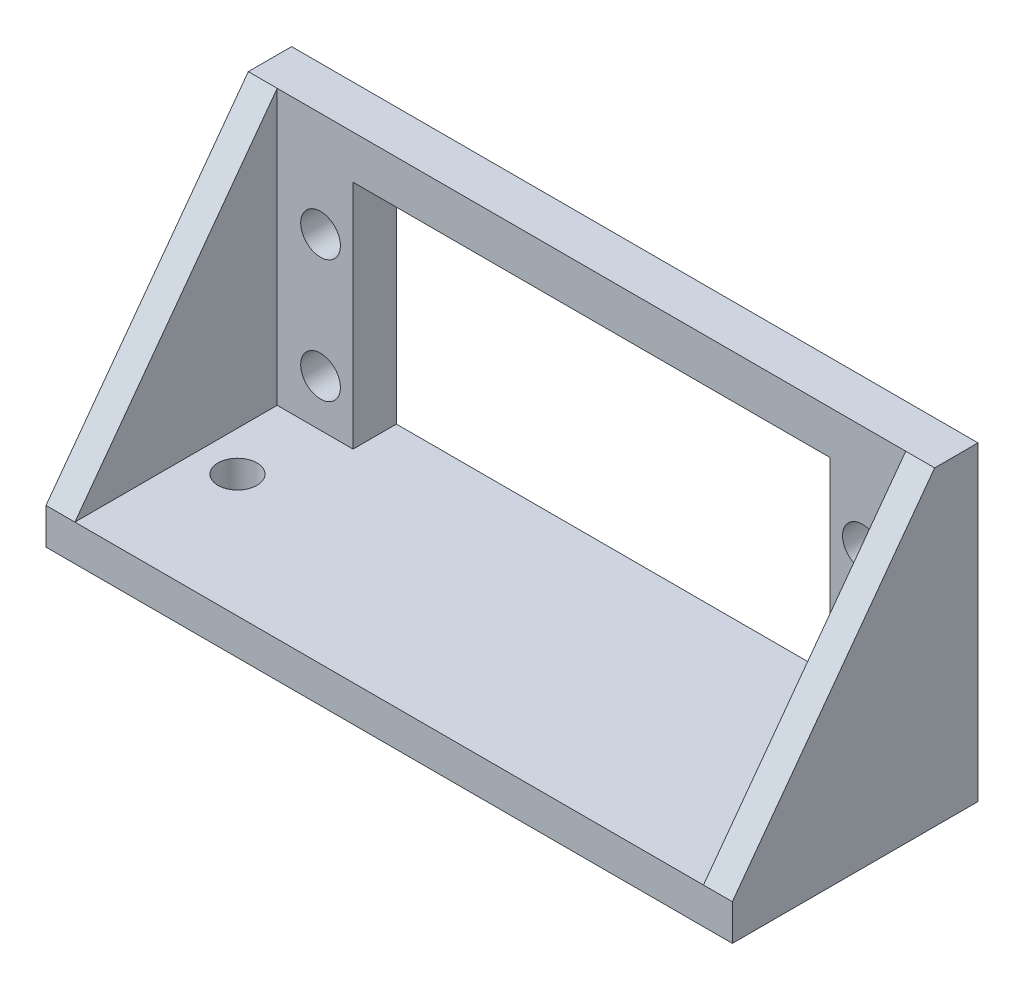
SolidWorks part; units mm, degrees
material "ABS PC"
ref_plane "Front Plane" through (0, 0, 0) normal (0, 0, 1) x (1, 0, 0)
ref_plane "Top Plane" through (0, 0, 0) normal (0, 1, 0) x (1, 0, 0)
ref_plane "Right Plane" through (0, 0, 0) normal (1, 0, 0) x (0, 0, -1)
sketch "Sketch1" plane through (0, 0, 0) normal (0, 1, 0) x (1, 0, 0)
  line L1 (-47.5, 17) -> (47.5, 17)
  line L2 (-47.5, 17) -> (-47.5, -17)
  line L3 (-47.5, -17) -> (47.5, -17)
  line L4 (47.5, 17) -> (47.5, -17)
  line L5 (-47.5, 17) -> (47.5, -17) construction
  line L6 (-47.5, -17) -> (47.5, 17) construction
  point P0 (0, 0)
  dimension "D1" = 95
  dimension "D2" = 34
extrude "Boss-Extrude1" add sketch "Sketch1" along normal blind 5
sketch "Sketch2" plane through (0, 5, 0) normal (0, 1, 0) x (1, 0, 0)
  line L0 (0, 17) -> (0, -17) construction
  line L1 (-47.5, -17) -> (47.5, -17) construction
  line L2 (-33, 17) -> (-33, -17) construction
  line L3 (47.5, 17) -> (-47.5, 17) construction
  line L4 (-47.5, 17) -> (-47.5, -17) construction
  line L5 (-33, 17) -> (-47.5, 17)
  line L6 (-33, 17) -> (-33, 11)
  line L7 (-33, 11) -> (-47.5, 11)
  line L8 (-47.5, 17) -> (-47.5, 11)
  line L9 (33, 11) -> (47.5, 11)
  line L10 (47.5, 17) -> (47.5, 11)
  line L11 (33, 17) -> (47.5, 17)
  line L12 (33, 17) -> (33, 11)
  point P6 (0, 0)
  dimension "D1" = 33
  dimension "D2" = 6
extrude "Boss-Extrude2" add sketch "Sketch2" along normal blind 38
sketch "Sketch3" plane through (0, 43, 0) normal (0, 1, 0) x (1, 0, 0)
  line L1 (-47.5, 17) -> (47.5, 17)
  line L2 (-47.5, 17) -> (-47.5, 11)
  line L3 (-47.5, 11) -> (47.5, 11)
  line L4 (47.5, 17) -> (47.5, 11)
extrude "Boss-Extrude3" add sketch "Sketch3" against normal blind 6
sketch "Sketch4" plane through (0, 0, -17) normal (0, 0, -1) x (-1, 0, 0)
  line L0 (0, 0) -> (0, 43) construction
  line L1 (-47.5, 43) -> (47.5, 43) construction
  line L2 (-33, 5) -> (33, 5) construction
  line L3 (33, 37) -> (33, 5) construction
  circle A0 centre (37.5, 11.5) radius 2.75
  circle A1 centre (37.5, 28.5) radius 2.75
  circle A2 centre (-37.5, 28.5) radius 2.75
  circle A3 centre (-37.5, 11.5) radius 2.75
  dimension "D1" = 5.5
  dimension "D4" = 5.5
  dimension "D2" = 6.5
  dimension "D3" = 37.5
  dimension "D5" = 17
extrude "Cut-Extrude1" cut sketch "Sketch4" against normal blind 6
sketch "Sketch6" plane through (0, 5, 0) normal (0, 1, 0) x (1, 0, 0)
  line L0 (-47.5, -17) -> (47.5, -17) construction
  line L2 (0, 0) -> (0, -17) construction
  circle A0 centre (-38, 0) radius 2.7
  circle A1 centre (38, 0) radius 2.7
  dimension "D1" = 17
  dimension "D2" = 76
extrude "Cut-Extrude2" cut sketch "Sketch6" against normal blind 6
sketch "Sketch7" plane through (-47.5, 0, 0) normal (-1, 0, 0) x (0, 0, 1)
  line L0 (17, 5) -> (-11, 43)
  line L1 (-11, 43) -> (-11, 5)
  line L2 (-11, 5) -> (17, 5)
extrude "Boss-Extrude4" add sketch "Sketch7" against normal blind 4
mirror "Mirror1" about plane through (0, 0, 0) normal (1, 0, 0) of "Boss-Extrude4"
